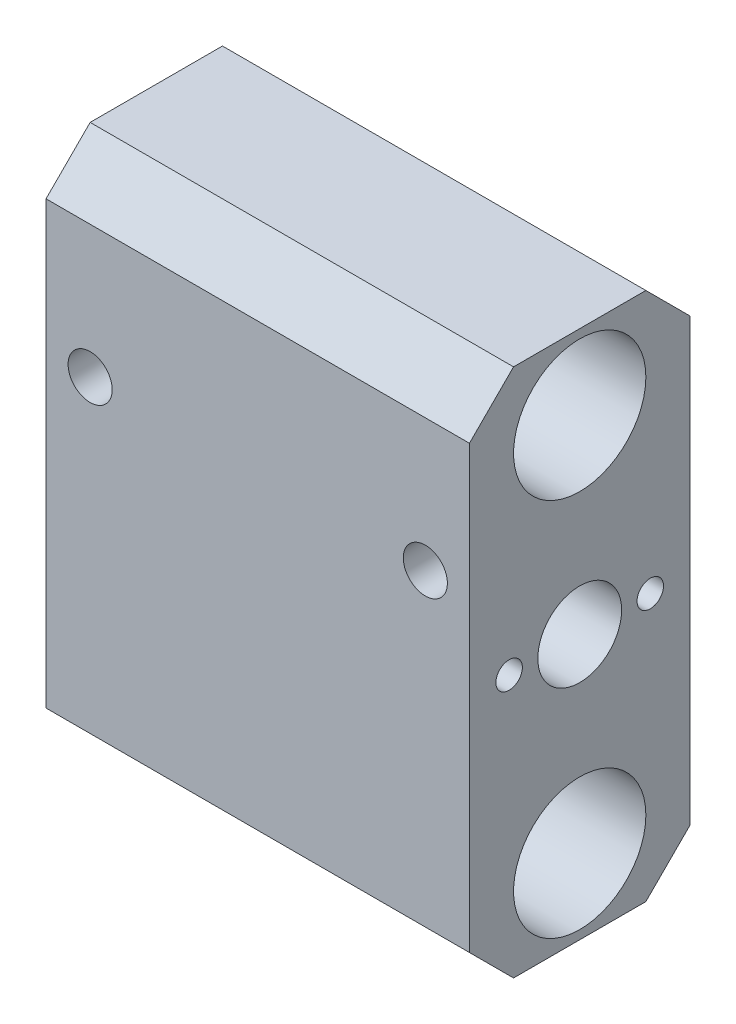
SolidWorks part; units mm, degrees
ref_plane "前视基准面" through (0, 0, 0) normal (0, 0, 1) x (1, 0, 0)
ref_plane "上视基准面" through (0, 0, 0) normal (0, 1, 0) x (1, 0, 0)
ref_plane "右视基准面" through (0, 0, 0) normal (1, 0, 0) x (0, 0, -1)
sketch "草图1" plane through (0, 0, 0) normal (1, 0, 0) x (0, 0, -1)
  line L1 (12.5, 30) -> (-12.5, 30)
  line L2 (12.5, 30) -> (12.5, -30)
  line L3 (12.5, -30) -> (-12.5, -30)
  line L4 (-12.5, 30) -> (-12.5, -30)
  line L5 (12.5, 30) -> (-12.5, -30) construction
  line L6 (12.5, -30) -> (-12.5, 30) construction
  circle A0 centre (0, 0) radius 4.75
  circle A1 centre (0, 21.5) radius 7.5
  circle A2 centre (0, -21.5) radius 7.5
  dimension "D1" = 43
  dimension "D3" = 60
  dimension "D2" = 21.5
  dimension "D4" = 25
extrude "凸台-拉伸1" add sketch "草图1" along normal blind 48
sketch "草图2" plane through (0, 0, 0) normal (-1, 0, 0) x (0, 0, 1)
  circle A1 centre (8, 0) radius 1.5
  circle A2 centre (-8, 0) radius 1.5
  point P8 (0, 0)
  dimension "D1" = 8
  dimension "D2" = 2
extrude "切除-拉伸1" cut sketch "草图2" against normal blind 10
sketch "草图3" plane through (48, 0, 0) normal (1, 0, 0) x (0, 0, -1)
  circle A0 centre (8, 0) radius 1.5
  circle A1 centre (-8, 0) radius 1.5
  point P2 (0, 0)
  point P7 (0, 0)
  dimension "D1" = 8
  dimension "D2" = 2
extrude "切除-拉伸2" cut sketch "草图3" against normal blind 10
chamfer "倒角1" distance 5 angle 45 4 edges at (24, -30, -12.5) (24, -30, 12.5) (24, 30, 12.5) (24, 30, -12.5)
sketch "草图4" plane through (0, 0, 12.5) normal (0, 0, 1) x (1, 0, 0)
  line L0 (0, 10) -> (48, 10) construction
  line L1 (0, 25) -> (0, -25) construction
  line L2 (48, 25) -> (48, -25) construction
  line L3 (24, 25) -> (24, -25) construction
  line L4 (48, 25) -> (0, 25) construction
  line L5 (0, -25) -> (48, -25) construction
  line L6 (0, 30) -> (48, 30) construction
  circle A0 centre (5, 10) radius 2.5
  circle A1 centre (43, 10) radius 2.5
  dimension "D1" = 19
  dimension "D2" = 20
extrude "切除-拉伸3" cut sketch "草图4" against normal blind 5
sketch "草图5" plane through (0, 0, -12.5) normal (0, 0, -1) x (-1, 0, 0)
  line L0 (-48, 0) -> (0, 0) construction
  line L1 (-48, -25) -> (-48, 25) construction
  line L2 (0, -25) -> (0, 25) construction
  line L3 (-10, 25) -> (-10, -25) construction
  line L4 (0, 25) -> (-48, 25) construction
  line L5 (-48, -25) -> (0, -25) construction
  circle A0 centre (-10, 9.5) radius 1.5
  circle A1 centre (-10, -9.5) radius 1.5
  dimension "D1" = 9.5
  dimension "D2" = 10
extrude "切除-拉伸4" cut sketch "草图5" against normal blind 5
